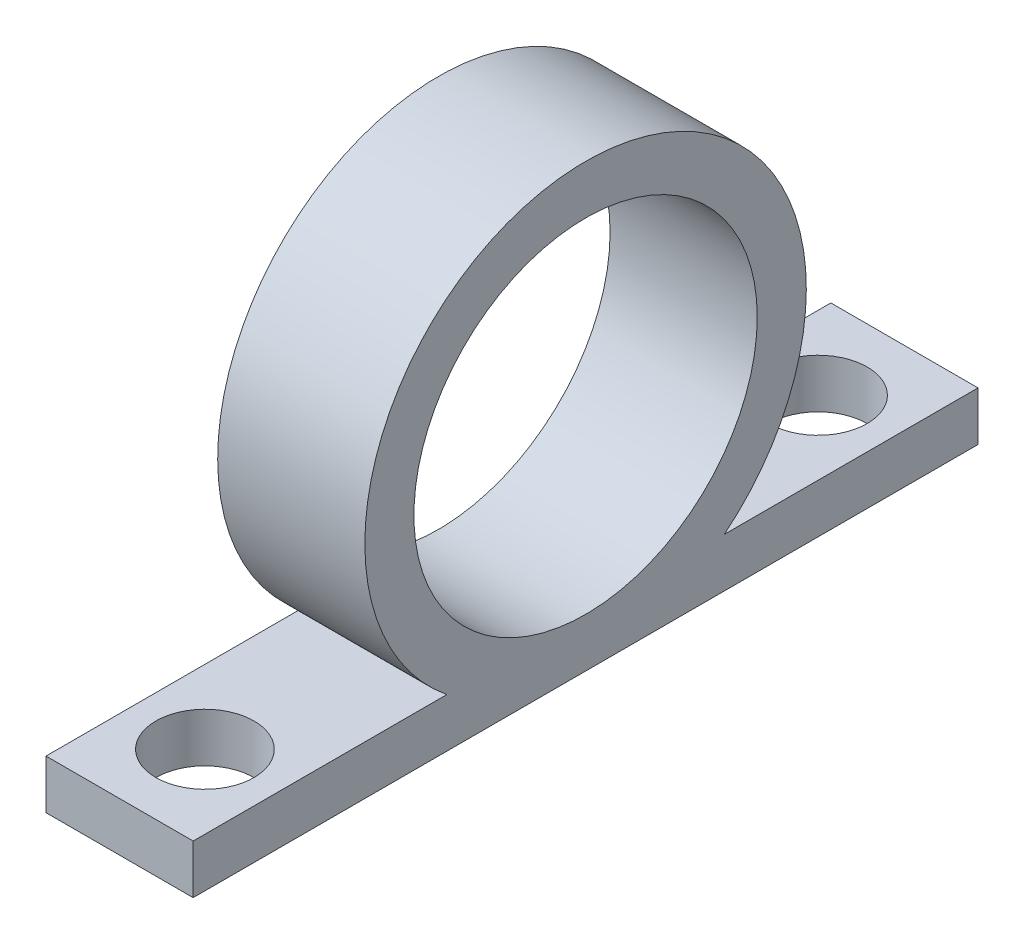
SolidWorks part; units mm, degrees
ref_plane "Front Plane" through (0, 0, 0) normal (0, 0, 1) x (1, 0, 0)
ref_plane "Top Plane" through (0, 0, 0) normal (0, 1, 0) x (1, 0, 0)
ref_plane "Right Plane" through (0, 0, 0) normal (1, 0, 0) x (0, 0, -1)
sketch "Sketch1" plane through (0, 0, 0) normal (1, 0, 0) x (0, 0, -1)
  line L1 (0, -45) -> (80, -45)
  line L2 (28.2843, -35) -> (80, -35)
  line L3 (80, -35) -> (80, -45)
  line L4 (0, -45) -> (-80, -45)
  line L5 (-80, -45) -> (-80, -35)
  line L6 (-80, -35) -> (-28.2843, -35)
  circle A0 centre (0, 0) radius 35
  arc A1 (28.2843, -35) -> (-28.2843, -35) centre (0, 0) ccw
  dimension "D1" = 70
  dimension "D2" = 90
  dimension "D3" = 80
  dimension "D4" = 80
extrude "Boss-Extrude1" add sketch "Sketch1" along normal blind 30
sketch "Sketch2" plane through (0, -35, 0) normal (0, 1, 0) x (1, 0, 0)
  circle A0 centre (15, 62.3994) radius 10
  circle A1 centre (15, -62.6006) radius 10
  dimension "D1" = 20
  dimension "D2" = 2
extrude "Cut-Extrude1" cut sketch "Sketch2" against normal blind 30
